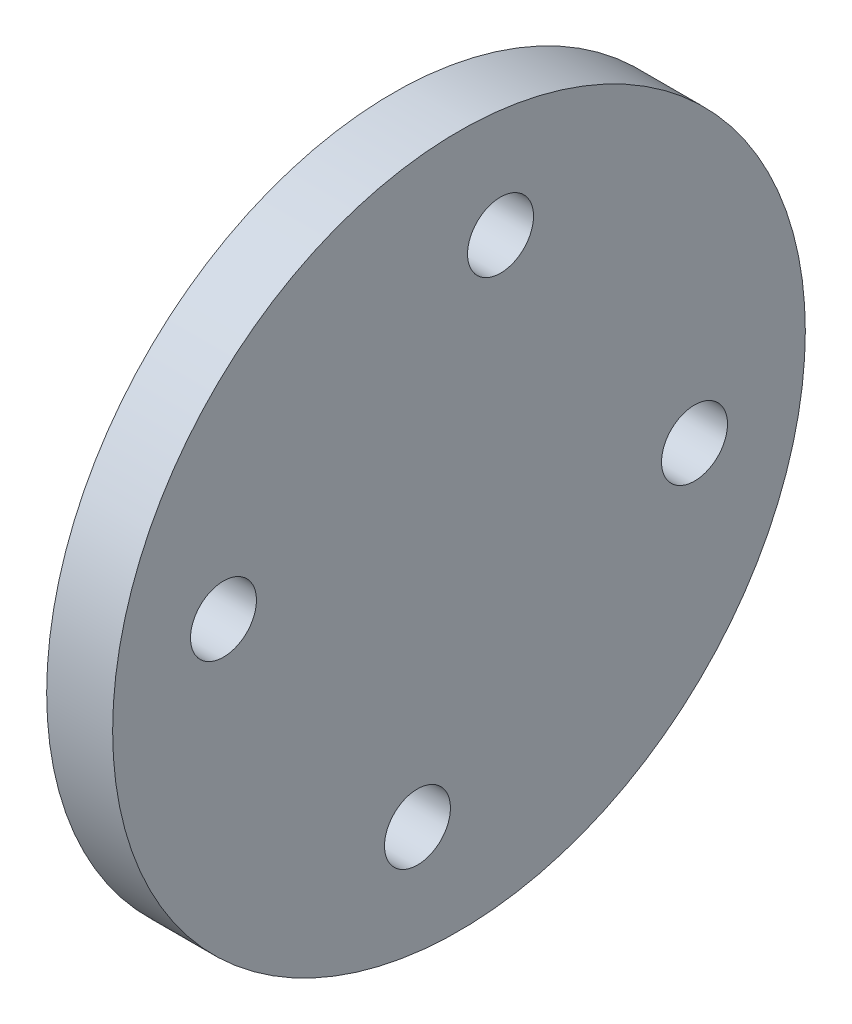
SolidWorks part; units mm, degrees
ref_plane "Front Plane" through (0, 0, 0) normal (0, 0, 1) x (1, 0, 0)
ref_plane "Top Plane" through (0, 0, 0) normal (0, 1, 0) x (1, 0, 0)
ref_plane "Right Plane" through (0, 0, 0) normal (1, 0, 0) x (0, 0, -1)
ref_plane "Plane1" through (48, 0, 0) normal (-1, 0, 0) x (0, -1, 0)
sketch "Sketch1" plane through (48, 0, 0) normal (-1, 0, 0) x (0, -1, 0)
  circle A0 centre (2.3561, -40.6576) radius 10.5
  circle A1 centre (-4.7838, -41.9166) radius 1
  circle A2 centre (9.4959, -39.3987) radius 1
  circle A3 centre (1.0971, -33.5178) radius 1
  circle A4 centre (3.615, -47.7975) radius 1
extrude "Boss-Extrude1" add sketch "Sketch1" against normal blind 2
